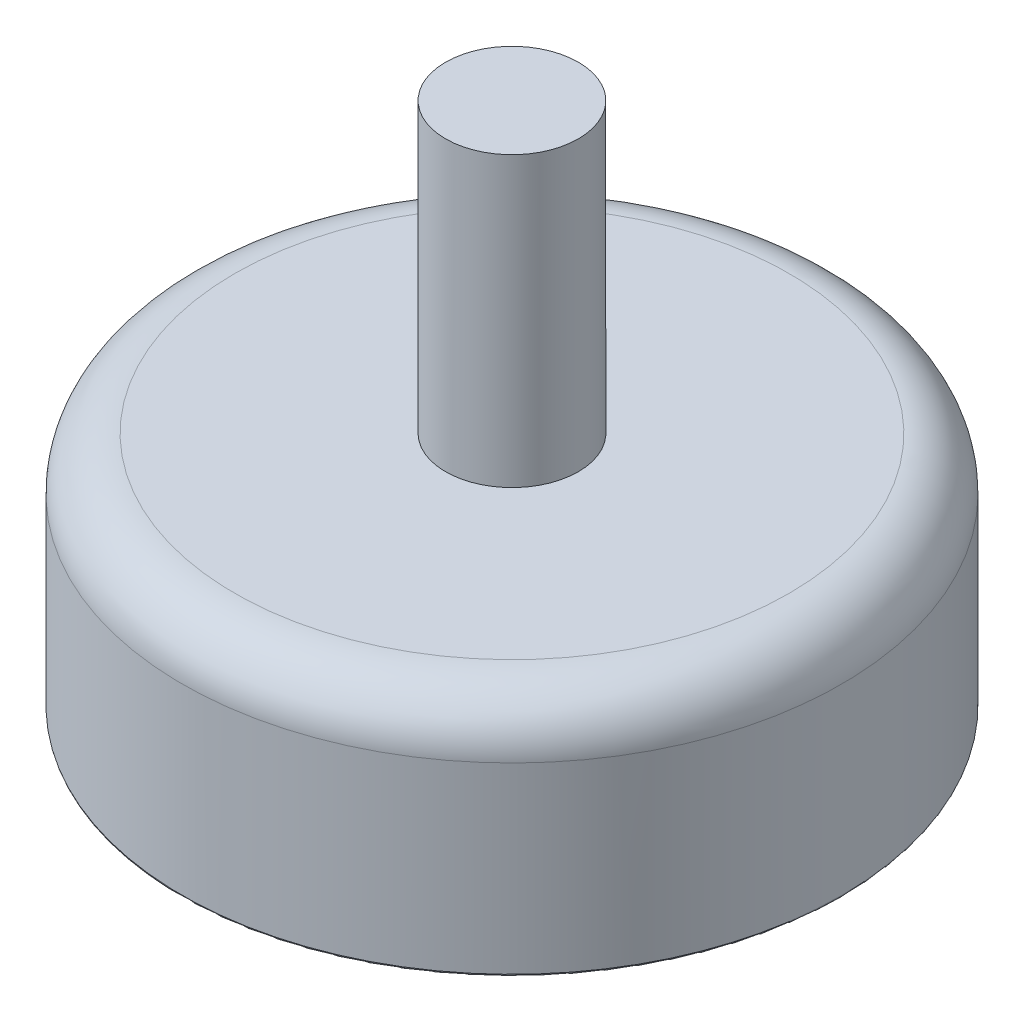
SolidWorks part; units mm, degrees
ref_plane "Front Plane" through (0, 0, 0) normal (0, 0, 1) x (1, 0, 0)
ref_plane "Top Plane" through (0, 0, 0) normal (0, 1, 0) x (1, 0, 0)
ref_plane "Right Plane" through (0, 0, 0) normal (1, 0, 0) x (0, 0, -1)
sketch "Sketch1" plane through (0, 0, 0) normal (0, 0, 1) x (1, 0, 0)
  line L0 (-8.16, 0) -> (-8.16, 0.6)
  line L1 (-7.93, 6.8) -> (0, 6.8)
  line L2 (-9.43, 5.3) -> (-9.43, 0)
  line L3 (-9.43, 0) -> (0, 0)
  line L4 (0, 6.8) -> (0, 0)
  line L5 (-9.43, 6.8) -> (0, 0) construction
  line L6 (-9.43, 0) -> (0, 6.8) construction
  line L7 (-8.16, 0.6) -> (-6.8, 0.6)
  line L8 (-6.8, 0.6) -> (-6.8, 0.5)
  line L9 (-6.8, 0.5) -> (0, 0.5)
  arc A0 (-7.93, 6.8) -> (-9.43, 5.3) centre (-7.93, 5.3) ccw
  dimension "D3" = 1.5
  dimension "D1" = 9.43
  dimension "D2" = 6.8
  dimension "D4" = 6.8
  dimension "D5" = 1.27
  dimension "D6" = 0.5
  dimension "D7" = 0.6
revolve "Revolve1" add sketch "Sketch1" angle 360 about L4
sketch "Sketch2" plane through (0, 6.8, 0) normal (0, 1, 0) x (1, 0, 0)
  circle A0 centre (0, 0) radius 1.9
  point P2 (0, 0)
  dimension "D1" = 3.8
extrude "Boss-Extrude1" add sketch "Sketch2" along normal blind 8.25
fillet "Fillet1" radius 0.0635 4 edges at (-6.8, 0.5, 0) (-9.43, 0, 0) (-8.16, 0.6, 0) (-8.16, 0, 0)
